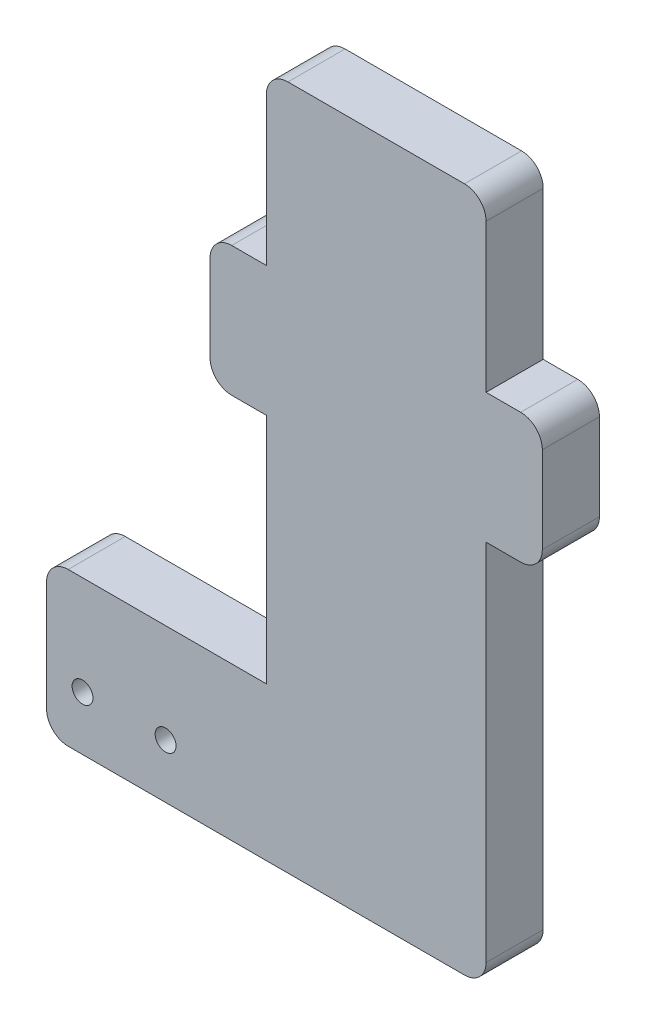
SolidWorks part; units mm, degrees
ref_plane "Front Plane" through (0, 0, 0) normal (0, 0, 1) x (1, 0, 0)
ref_plane "Top Plane" through (0, 0, 0) normal (0, 1, 0) x (1, 0, 0)
ref_plane "Right Plane" through (0, 0, 0) normal (1, 0, 0) x (0, 0, -1)
sketch "Model" plane through (0, 0, 0) normal (0, 0, 1) x (1, 0, 0)
  line L0 (-38.1, -33.25) -> (-38.1, -45.95)
  line L1 (-12.7, -30.75) -> (-35.6, -30.75)
  line L2 (-16.7, -3.87) -> (-12.7, -3.87)
  line L3 (-19.2, 8.63) -> (-19.2, -1.37)
  line L4 (-12.7, 11.13) -> (-16.7, 11.13)
  line L5 (-12.7, 28.25) -> (-12.7, 11.13)
  line L6 (10.2, 30.75) -> (-10.2, 30.75)
  line L7 (19.2, 8.63) -> (19.2, -1.37)
  line L8 (-35.6, -48.45) -> (10.2, -48.45)
  line L9 (12.7, 11.13) -> (16.7, 11.13)
  line L10 (12.7, -45.95) -> (12.7, -3.87)
  line L11 (16.7, -3.87) -> (12.7, -3.87)
  line L12 (-12.7, -3.87) -> (-12.7, -30.75)
  line L13 (12.7, 11.13) -> (12.7, 28.25)
  circle A0 centre (-33.9438, -42.1983) radius 1.2065
  circle A1 centre (-24.3426, -42.1983) radius 1.2065
  arc A2 (-38.1, -45.95) -> (-35.6, -48.45) centre (-35.6, -45.95) ccw
  arc A3 (-35.6, -30.75) -> (-38.1, -33.25) centre (-35.6, -33.25) ccw
  arc A4 (-19.2, -1.37) -> (-16.7, -3.87) centre (-16.7, -1.37) ccw
  arc A5 (-16.7, 11.13) -> (-19.2, 8.63) centre (-16.7, 8.63) ccw
  arc A6 (-10.2, 30.75) -> (-12.7, 28.25) centre (-10.2, 28.25) ccw
  arc A7 (12.7, 28.25) -> (10.2, 30.75) centre (10.2, 28.25) ccw
  arc A8 (19.2, 8.63) -> (16.7, 11.13) centre (16.7, 8.63) ccw
  arc A9 (16.7, -3.87) -> (19.2, -1.37) centre (16.7, -1.37) ccw
  arc A10 (10.2, -48.45) -> (12.7, -45.95) centre (10.2, -45.95) ccw
extrude "Boss-Extrude1" add sketch "Model" along normal blind 6.6
